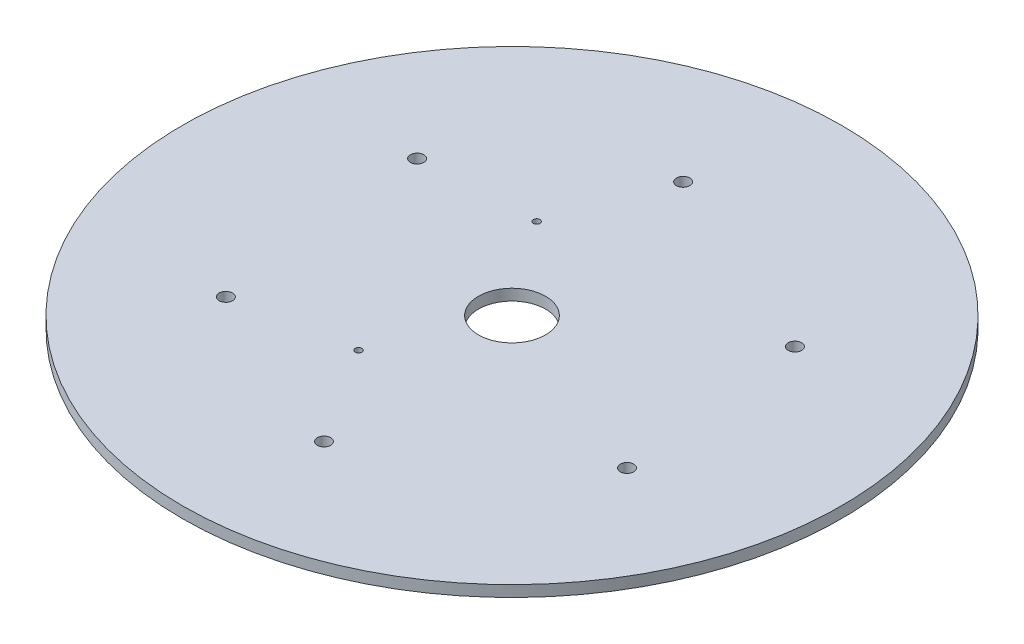
SolidWorks part; units mm, degrees
ref_plane "Plan de face" through (0, 0, 0) normal (0, 0, 1) x (1, 0, 0)
ref_plane "Plan de dessus" through (0, 0, 0) normal (0, 1, 0) x (1, 0, 0)
ref_plane "Plan de droite" through (0, 0, 0) normal (1, 0, 0) x (0, 0, -1)
sketch "Esquisse1" plane through (0, 0, 0) normal (0, 1, 0) x (1, 0, 0)
  line L0 (-71.2823, -56.7896) -> (6.7402, -90.8889) construction
  line L1 (-71.2823, -56.7896) -> (-20.8897, -47.7977) construction
  line L2 (-20.8897, -47.7977) -> (6.7402, -90.8889) construction
  line L3 (-20.8897, -47.7977) -> (-32.271, -73.8393) construction
  line L4 (-82.0822, 39.6073) -> (-13.5401, 90.1271) construction
  line L5 (-13.5401, 90.1271) -> (-30.9492, 41.9899) construction
  line L6 (-30.9492, 41.9899) -> (-82.0822, 39.6073) construction
  line L7 (-47.8112, 64.8672) -> (-30.9492, 41.9899) construction
  circle A1 centre (0, 0) radius 15
  circle A10 centre (-13.5401, 90.1271) radius 3
  circle A11 centre (-82.0822, 39.6073) radius 3
  circle A12 centre (75.342, 51.2816) radius 3
  circle A13 centre (84.8224, -33.3375) radius 3
  circle A14 centre (6.7402, -90.8889) radius 3
  circle A15 centre (-71.2823, -56.7896) radius 3
  circle A16 centre (0, 0) radius 91.1385 construction
  circle A18 centre (0, 0) radius 147.5
  circle A19 centre (-20.8897, -47.7977) radius 1.5
  circle A20 centre (-30.9492, 41.9899) radius 1.5
  dimension "D2" = 30
  dimension "D3" = 295
  dimension "D4" = 6
  dimension "D6" = 85.1485
  dimension "D5" = 97
  dimension "D7" = 97
  dimension "D8" = 85.1485
  dimension "D9" = 97
  dimension "D10" = 182.277
  dimension "D12" = 3
  dimension "D14" = 3
  dimension "D11" = 28.42
  dimension "D13" = 28.42
extrude "Boss.-Extru.1" add sketch "Esquisse1" along normal blind 5
